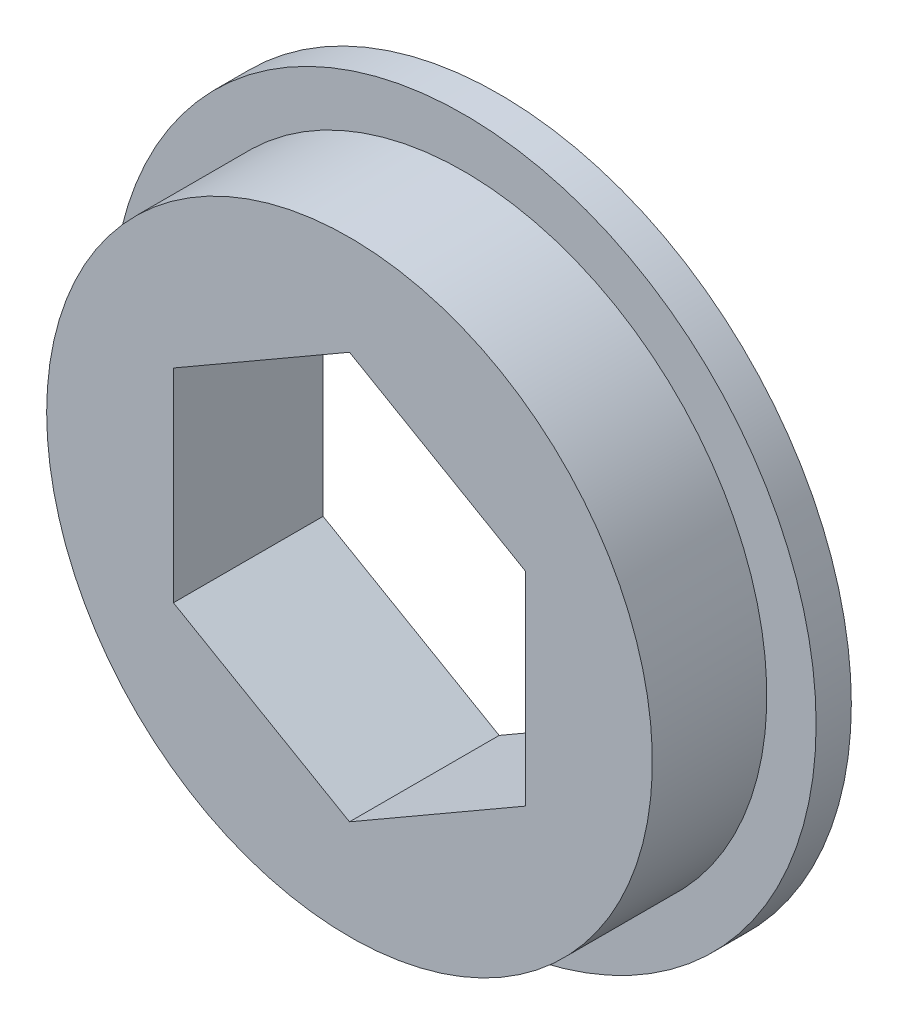
SolidWorks part; units mm, degrees
ref_plane "Front Plane" through (0, 0, 0) normal (0, 0, 1) x (1, 0, 0)
ref_plane "Top Plane" through (0, 0, 0) normal (0, 1, 0) x (1, 0, 0)
ref_plane "Right Plane" through (0, 0, 0) normal (1, 0, 0) x (0, 0, -1)
sketch "Sketch1" plane through (0, 0, 0) normal (0, 0, 1) x (1, 0, 0)
  circle A0 centre (0, 0) radius 20
  dimension "D1" = 40
extrude "Boss-Extrude1" add sketch "Sketch1" along normal blind 2
sketch "Sketch2" plane through (0, 0, 2) normal (0, 0, 1) x (1, 0, 0)
  circle A0 centre (0, 0) radius 17.2
  dimension "D1" = 34.4
extrude "Boss-Extrude2" add sketch "Sketch2" along normal blind 6.5
sketch "Sketch3" plane through (0, 0, 8.5) normal (0, 0, 1) x (1, 0, 0)
  line L0 (0, 22.6474) -> (0, -23.3502) construction
  line L2 (0, 11.547) -> (-10, 5.7735)
  line L3 (-10, 5.7735) -> (-10, -5.7735)
  line L4 (-10, -5.7735) -> (0, -11.547)
  line L5 (0, -11.547) -> (10, -5.7735)
  line L6 (10, -5.7735) -> (10, 5.7735)
  line L7 (10, 5.7735) -> (0, 11.547)
  circle A0 centre (0, 0) radius 10 construction
  dimension "D1" = 20
extrude "Cut-Extrude1" cut sketch "Sketch3" against normal through all
